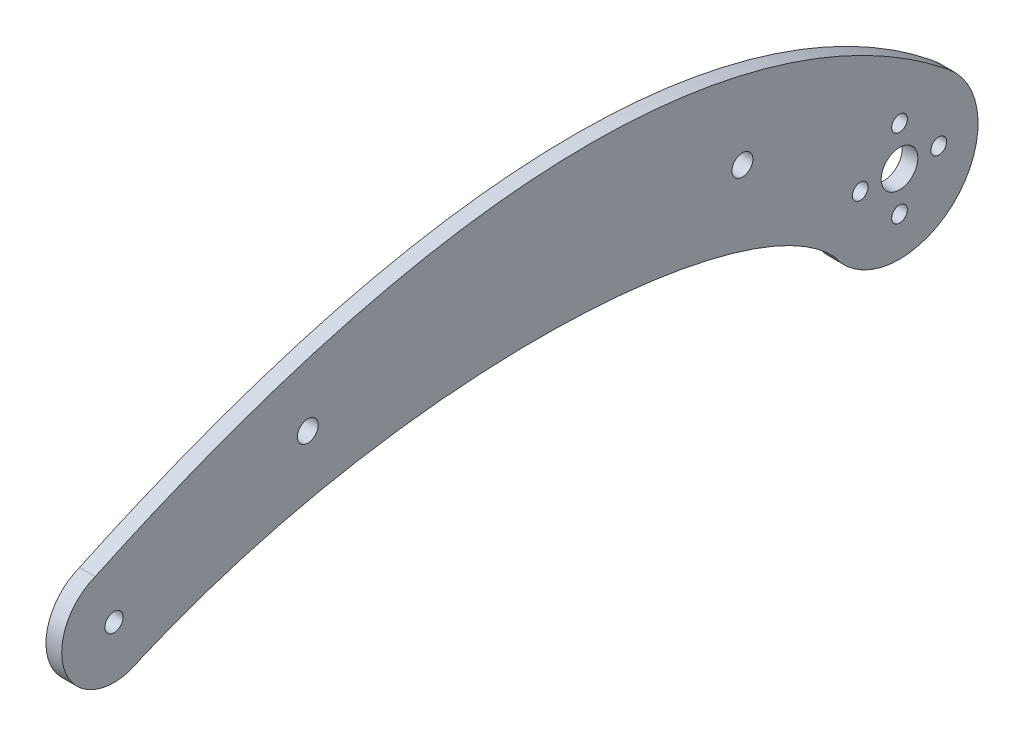
SolidWorks part; units mm, degrees
ref_plane "Alzado" through (0, 0, 0) normal (0, 0, 1) x (1, 0, 0)
ref_plane "Planta" through (0, 0, 0) normal (0, 1, 0) x (1, 0, 0)
ref_plane "Vista lateral" through (0, 0, 0) normal (1, 0, 0) x (0, 0, -1)
sketch "Croquis1" plane through (0, 0, 0) normal (1, 0, 0) x (0, 0, -1)
  line L0 (0, 0) -> (-150, 0) construction
  arc A0 (-12.4798, -8.322) -> (9.282, 11.7833) centre (0, 0) ccw
  arc A1 (-153.5894, 9.3336) -> (-144.8946, -8.5985) centre (-150, 0) ccw
  circle A2 centre (-150, 0) radius 1.75
  circle A3 centre (0, 0) radius 3.5
  circle A4 centre (-113, 13.1172) radius 2
  circle A5 centre (-30, 15.6148) radius 2
  circle A7 centre (-7.5, 0) radius 1.5
  circle A8 centre (0, -7.5) radius 1.5
  circle A9 centre (0, 7.5) radius 1.5
  circle A10 centre (7.5, 0) radius 1.5
  spline S0 degree 3 poles (-144.8946, -8.5985) (-94.3996, 13.0893) (-29.0218, 9.6082) (-12.4798, -8.322) knots 0 0 0 0 1 1 1 1
  spline S1 degree 3 poles (-153.5894, 9.3336) (-52.0275, 57.0175) (-3.0287, 21.6661) (9.282, 11.7833) knots 0 0 0 0 1 1 1 1
  dimension "D1" = 3.5
  dimension "D2" = 4
  dimension "D3" = 9.282
  dimension "D4" = 12.4798
  dimension "D5" = 30
  dimension "D6" = 113
  dimension "D7" = 144.8946
  dimension "D8" = 153.5894
  dimension "D9" = 13.1172
  dimension "D10" = 15.6148
extrude "Saliente-Extruir1" add sketch "Croquis1" along normal blind 3
